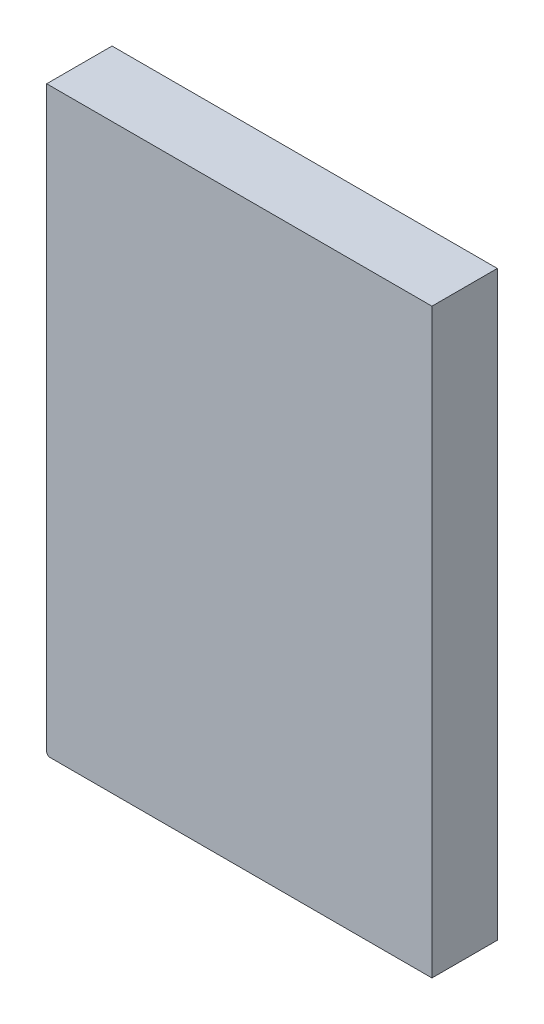
SolidWorks part; units mm, degrees
ref_plane "Front Plane" through (0, 0, 0) normal (0, 0, 1) x (1, 0, 0)
ref_plane "Top Plane" through (0, 0, 0) normal (0, 1, 0) x (1, 0, 0)
ref_plane "Right Plane" through (0, 0, 0) normal (1, 0, 0) x (0, 0, -1)
sketch "Sketch1" plane through (0, 0, 0) normal (0, 0, 1) x (1, 0, 0)
  line L1 (0, 0) -> (700, 0)
  line L2 (0, 0) -> (0, 900)
  line L3 (0, 900) -> (700, 900)
  line L4 (700, 0) -> (700, 900)
  dimension "D1" = 900
  dimension "D2" = 700
extrude "Boss-Extrude1" add sketch "Sketch1" along normal blind 100
sketch "Sketch2" plane through (0, 0, 100) normal (0, 0, 1) x (1, 0, 0)
  line L0 (700, 900) -> (0, 900) construction
  line L1 (597.1365, 900) -> (700, 900)
  line L2 (597.1365, 900) -> (597.1365, 0)
  line L3 (597.1365, 0) -> (700, 0)
  line L4 (700, 900) -> (700, 0)
  line L5 (700, 0) -> (700, 900) construction
  dimension "D1" = 102.8635
extrude "Cut-Extrude1" cut sketch "Sketch2" against normal through all
sketch "Sketch3" plane through (0, 0, 100) normal (0, 0, 1) x (1, 0, 0)
  line L0 (0, 5) -> (597.1365, 5)
  line L1 (0, 900) -> (0, 0) construction
  line L2 (597.1365, 900) -> (597.1365, 0) construction
  line L3 (597.1365, 5) -> (597.1365, 0)
  line L4 (597.1365, 0) -> (0, 0)
  line L5 (0, 0) -> (0, 5)
extrude "Cut-Extrude2" cut sketch "Sketch3" against normal through all contours L5 L0 L3 L4
fillet "Fillet1" radius 5 4 edges at (0, 900, 50) (597.1365, 900, 50) (597.1365, 5, 50) (0, 5, 50)
sketch "Sketch4" plane through (0, 0, 100) normal (0, 0, 1) x (1, 0, 0)
  line L1 (0, 895) -> (597.1365, 895)
  line L2 (0, 895) -> (0, 900)
  line L3 (0, 900) -> (597.1365, 900)
  line L4 (597.1365, 895) -> (597.1365, 900)
extrude "Cut-Extrude3" cut sketch "Sketch4" against normal through all
sketch "Sketch5" plane through (0, 0, 100) normal (0, 0, 1) x (1, 0, 0)
  line L0 (5, 5) -> (592.1365, 5) construction
  line L1 (589.3301, 5) -> (597.1365, 5)
  line L2 (589.3301, 5) -> (589.3301, 895)
  line L3 (589.3301, 895) -> (597.1365, 895)
  line L4 (597.1365, 5) -> (597.1365, 895)
extrude "Cut-Extrude4" cut sketch "Sketch5" against normal through all
